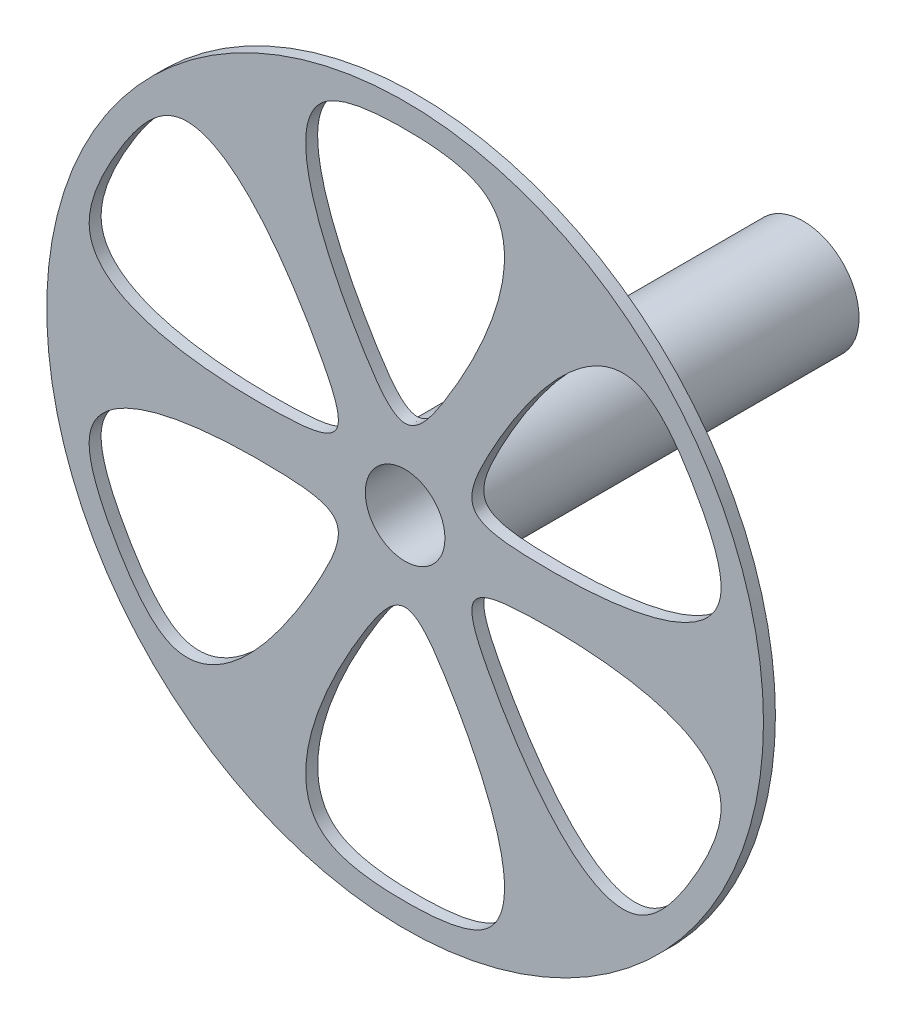
SolidWorks part; units mm, degrees
ref_plane "Front Plane" through (0, 0, 0) normal (0, 0, 1) x (1, 0, 0)
ref_plane "Top Plane" through (0, 0, 0) normal (0, 1, 0) x (1, 0, 0)
ref_plane "Right Plane" through (0, 0, 0) normal (1, 0, 0) x (0, 0, -1)
sketch "Sketch1" plane through (0, 0, 0) normal (0, 0, 1) x (1, 0, 0)
  circle A0 centre (0, 0) radius 45
  circle A1 centre (0, 0) radius 5
  spline S0 degree 3 poles (0, 7.5888) (-9.4939, 21.105) (-17.4812, 40.6332) (0, 42.3905) (17.4812, 40.6332) (9.4939, 21.105) (0, 7.5888) (-9.4939, 21.105) (-17.4812, 40.6332) knots -0.463439 -0.16535 -0.082675 0 0.298089 0.417325 0.536561 0.83465 0.917325 1 1.298089 1.417325 1.536561 only from (-5, 15) to (-5, 15)
  spline S1 degree 3 poles (6.5721, 3.7944) (13.5305, 18.7745) (26.4488, 35.4558) (36.7113, 21.1953) (43.93, 5.1774) (23.0244, 2.3305) (6.5721, 3.7944) (13.5305, 18.7745) (26.4488, 35.4558) knots -0.463439 -0.16535 -0.082675 0 0.298089 0.417325 0.536561 0.83465 0.917325 1 1.298089 1.417325 1.536561 only from (10.4904, 11.8301) to (10.4904, 11.8301)
  spline S2 degree 3 poles (6.5721, -3.7944) (23.0244, -2.3305) (43.93, -5.1774) (36.7113, -21.1953) (26.4488, -35.4558) (13.5305, -18.7745) (6.5721, -3.7944) (23.0244, -2.3305) (43.93, -5.1774) knots -0.463439 -0.16535 -0.082675 0 0.298089 0.417325 0.536561 0.83465 0.917325 1 1.298089 1.417325 1.536561 only from (15.4904, -3.1699) to (15.4904, -3.1699)
  spline S3 degree 3 poles (0, -7.5888) (9.4939, -21.105) (17.4812, -40.6332) (0, -42.3905) (-17.4812, -40.6332) (-9.4939, -21.105) (0, -7.5888) (9.4939, -21.105) (17.4812, -40.6332) knots -0.463439 -0.16535 -0.082675 0 0.298089 0.417325 0.536561 0.83465 0.917325 1 1.298089 1.417325 1.536561 only from (5, -15) to (5, -15)
  spline S4 degree 3 poles (-6.5721, -3.7944) (-13.5305, -18.7745) (-26.4488, -35.4558) (-36.7113, -21.1953) (-43.93, -5.1774) (-23.0244, -2.3305) (-6.5721, -3.7944) (-13.5305, -18.7745) (-26.4488, -35.4558) knots -0.463439 -0.16535 -0.082675 0 0.298089 0.417325 0.536561 0.83465 0.917325 1 1.298089 1.417325 1.536561 only from (-10.4904, -11.8301) to (-10.4904, -11.8301)
  spline S5 degree 3 poles (-6.5721, 3.7944) (-23.0244, 2.3305) (-43.93, 5.1774) (-36.7113, 21.1953) (-26.4488, 35.4558) (-13.5305, 18.7745) (-6.5721, 3.7944) (-23.0244, 2.3305) (-43.93, 5.1774) knots -0.463439 -0.16535 -0.082675 0 0.298089 0.417325 0.536561 0.83465 0.917325 1 1.298089 1.417325 1.536561 only from (-15.4904, 3.1699) to (-15.4904, 3.1699)
  point P41 (0, 0)
  point P43 (0, 0)
  point P44 (0, 0)
  dimension "D1" = 90
  dimension "D13" = 10
  dimension "D2" = 42
  dimension "D3" = 40
  dimension "D4" = 40
  dimension "D5" = 15
  dimension "D6" = 15
  dimension "D7" = 0
  dimension "D8" = 5
  dimension "D9" = 5
  dimension "D10" = 10
  dimension "D11" = 10
  dimension "D12" = 10
extrude "Boss-Extrude1" add sketch "Sketch1" along normal blind 1.5
sketch "Sketch2" plane through (0, 0, 1.5) normal (0, 0, 1) x (1, 0, 0)
  circle A0 centre (0, 0) radius 7
  circle A1 centre (0, 0) radius 5
  dimension "D1" = 10
  dimension "D2" = 14
extrude "Boss-Extrude2" add sketch "Sketch2" against normal blind 50
